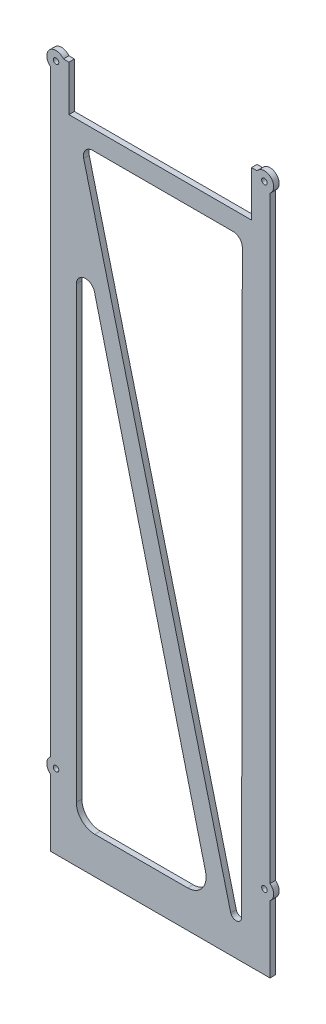
SolidWorks part; units mm, degrees
ref_plane "前视基准面" through (0, 0, 0) normal (0, 0, 1) x (1, 0, 0)
ref_plane "上视基准面" through (0, 0, 0) normal (0, 1, 0) x (1, 0, 0)
ref_plane "右视基准面" through (0, 0, 0) normal (1, 0, 0) x (0, 0, -1)
sketch "草图1" plane through (0, 0, 0) normal (0, 0, 1) x (1, 0, 0)
  line L0 (0, 0) -> (113, 0) construction
  line L4 (-3, 3) -> (116, 3) construction
  line L8 (-3, -336.18) -> (-3, -372.5013)
  line L10 (116, -328.18) -> (116, -4)
  line L11 (109, 3) -> (4, 3) construction
  line L12 (-3, -4) -> (-3, -328.18)
  line L15 (7, -27) -> (7, 3) construction
  line L16 (7, -27) -> (106, -27) construction
  line L17 (106, -27) -> (106, 3) construction
  line L18 (106, 3) -> (109, 3)
  line L19 (7, 3) -> (4, 3)
  line L20 (116, -372.5013) -> (-3, -372.5013)
  line L21 (116, -372.5013) -> (116, -336.18)
  line L22 (11, -99.1045) -> (11, -342.5249)
  line L23 (100.9882, -37.0059) -> (100.6156, -351.791)
  line L27 (21, -352.5249) -> (71.3855, -352.5249)
  line L28 (94.7076, -352.5249) -> (15.0058, -38.229)
  line L29 (81.0899, -340.1114) -> (20.8466, -97.8755)
  line L30 (19.8524, -32) -> (95.9882, -32)
  line L31 (7, -21.6458) -> (106, -21.6458)
  line L32 (7, 3) -> (7, -21.6458)
  line L33 (106, -21.6458) -> (106, 3)
  line L34 (100.9941, -32) -> (100.5873, -375.7107) construction
  line L35 (13.4262, -32) -> (100.9941, -32) construction
  line L36 (100.5873, -375.7107) -> (13.4262, -32) construction
  line L41 (106, -27) -> (105.5401, -415.5826) construction
  line L43 (105.5401, -415.5826) -> (7, -27) construction
  circle A0 centre (0, 0) radius 1.5
  circle A1 centre (113, 0) radius 1.5
  circle A4 centre (0, -332.18) radius 1.5
  circle A5 centre (113, -332.18) radius 1.5
  circle A6 centre (0, 0) radius 5 construction
  circle A7 centre (113, 0) radius 5 construction
  circle A10 centre (113, -332.18) radius 5 construction
  circle A11 centre (0, -332.18) radius 5 construction
  arc A14 (116, -336.18) -> (116, -328.18) centre (113, -332.18) ccw
  arc A15 (109, 3) -> (116, -4) centre (113, 0) cw
  arc A16 (4, 3) -> (-3, -4) centre (0, 0) ccw
  arc A17 (-3, -336.18) -> (-3, -328.18) centre (0, -332.18) cw
  arc A18 (100.9882, -37.0059) -> (95.9882, -32) centre (95.9882, -37) ccw
  arc A19 (15.0058, -38.229) -> (19.8524, -32) centre (19.8524, -37) cw
  arc A22 (11, -99.1045) -> (20.8466, -97.8755) centre (16, -99.1045) cw
  arc A23 (100.6156, -351.791) -> (94.7076, -352.5249) centre (97.6156, -351.7875) cw
  arc A24 (81.0899, -340.1114) -> (71.3855, -352.5249) centre (71.3855, -342.5249) cw
  arc A25 (21, -352.5249) -> (11, -342.5249) centre (21, -342.5249) cw
  point P12 (84.1771, -352.5249)
  dimension "D1" = 5
  dimension "D7" = 10
  dimension "D2" = 3
  dimension "D3" = 10
  dimension "D6" = 3
  dimension "D8" = 10
  dimension "D9" = 30
extrude "凸台-拉伸1" add sketch "草图1" along normal blind 3
